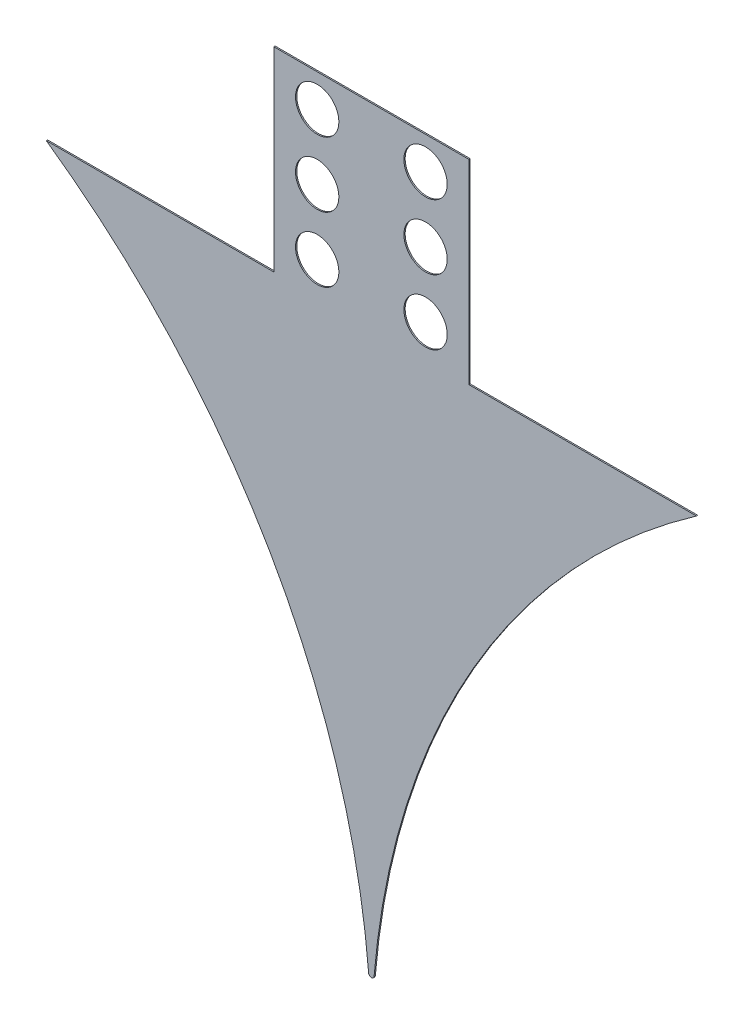
SolidWorks part; units mm, degrees
ref_plane "Front Plane" through (0, 0, 0) normal (0, 0, 1) x (1, 0, 0)
ref_plane "Top Plane" through (0, 0, 0) normal (0, 1, 0) x (1, 0, 0)
ref_plane "Right Plane" through (0, 0, 0) normal (1, 0, 0) x (0, 0, -1)
sketch "Sketch1" plane through (0, 0, 0) normal (0, 0, 1) x (1, 0, 0)
  line L0 (0, 145.9429) -> (0, -145.9429) construction
  line L1 (67, 50) -> (220, 50)
  line L2 (-67, 50) -> (-220, 50)
  line L3 (17.9555, 13) -> (15.1177, 40)
  line L4 (15.1177, 40) -> (12, 27.4955)
  line L5 (-15.1177, 40) -> (-12, 27.4955)
  line L6 (-17.9555, 13) -> (-15.1177, 40)
  line L7 (220, 50) -> (158.9525, 7.2541)
  line L8 (-220, 50) -> (-158.9525, 7.2541)
  line L9 (-140, -25) -> (-99.5632, -25)
  line L10 (140, -25) -> (99.5632, -25)
  arc A0 (67, 50) -> (17.9555, 13) centre (27.0477, 51.953) cw
  arc A1 (-67, 50) -> (-17.9555, 13) centre (-27.0477, 51.953) ccw
  arc A2 (12, 27.4955) -> (-12, 27.4955) centre (0, 0) ccw
  arc A3 (158.9525, 7.2541) -> (140, -25) centre (184.7635, -29.6077) ccw
  arc A4 (-99.5632, -25) -> (0, -115.6638) centre (-99.5632, -125) cw
  arc A5 (99.5632, -25) -> (0, -115.6638) centre (99.5632, -125) ccw
  arc A6 (-158.9525, 7.2541) -> (-140, -25) centre (-184.7635, -29.6077) cw
  dimension "D2" = 40
  dimension "D5" = 30
  dimension "D10" = 220
  dimension "D12" = 45
  dimension "D13" = 100
  dimension "D1" = 134
  dimension "D3" = 84
  dimension "D4" = 160
  dimension "D6" = 50
  dimension "D7" = 24
  dimension "D8" = 37
  dimension "D9" = 10
  dimension "D11" = 35
  dimension "D14" = 140
  dimension "D15" = 75
  dimension "D16" = 140
  dimension "D17" = 99.5632
sketch "Sketch2" plane through (0, 0, 0) normal (0, 0, 1) x (1, 0, 0)
  line L0 (0, 145.9429) -> (0, -145.9429) construction
  line L7 (0, 0) -> (0, -152.8683) construction
  line L8 (99.5632, -21.9265) -> (48.69, -83.15)
  line L9 (-99.5632, -21.9265) -> (-48.69, -83.15)
  line L26 (158.9525, 10.3276) -> (220, 53.0735)
  line L27 (220, 53.0735) -> (67, 53.0735)
  line L28 (17.9555, 16.0735) -> (15.1177, 43.0735)
  line L29 (15.1177, 43.0735) -> (12, 30.569)
  line L30 (-12, 30.569) -> (-15.1177, 43.0735)
  line L31 (-15.1177, 43.0735) -> (-17.9555, 16.0735)
  line L32 (-67, 53.0735) -> (-220, 53.0735)
  line L33 (-220, 53.0735) -> (-158.9525, 10.3276)
  line L34 (-140, -21.9265) -> (-99.5632, -21.9265)
  line L35 (99.5632, -21.9265) -> (140, -21.9265)
  circle A2 centre (46.19, 13) radius 1.5875
  circle A3 centre (-46.19, 13) radius 1.5875
  circle A4 centre (46.19, -80.65) radius 1.5875
  circle A5 centre (-46.19, -80.65) radius 1.5875
  arc A6 (48.69, -83.15) -> (0, -150) centre (70.2366, -150) ccw
  arc A7 (-48.69, -83.15) -> (0, -150) centre (-70.2366, -150) cw
  arc A14 (17.9555, 16.0735) -> (67, 53.0735) centre (27.0477, 55.0265) ccw
  arc A15 (12, 30.569) -> (-12, 30.569) centre (0, 3.0735) ccw
  arc A16 (-67, 53.0735) -> (-17.9555, 16.0735) centre (-27.0477, 55.0265) ccw
  arc A17 (-140, -21.9265) -> (-158.9525, 10.3276) centre (-184.7635, -26.5342) ccw
  arc A20 (158.9525, 10.3276) -> (140, -21.9265) centre (184.7635, -26.5342) ccw
  point P0 (0, 40)
  dimension "D3" = 93.65
  dimension "D4" = 3.175
  dimension "D5" = 3.175
  dimension "D6" = 3.175
  dimension "D7" = 3.175
  dimension "D2" = 40
  dimension "D9" = 25
  dimension "D10" = 46.19
  dimension "D11" = 27
  dimension "D12" = 46.19
  dimension "D13" = 99.5632
  dimension "D14" = 2.5
  dimension "D15" = 2.5
  dimension "D16" = 150
extrude "Boss-Extrude1" add sketch "Sketch2" along normal blind 0.118
sketch "Sketch3" plane through (0, 0, 0) normal (0, 0, -1) x (-1, 0, 0)
  line L0 (0, -121.719) -> (0, 0) construction
  line L1 (165, 49.5735) -> (165, 19.5735) construction
  line L2 (165, 19.5735) -> (165, 49.5735) construction
  line L3 (67, 53.0735) -> (220, 53.0735) construction
  circle A0 centre (165, 49.5735) radius 2
  circle A1 centre (165, 19.5735) radius 2
  circle A2 centre (150, 34.5735) radius 2
  dimension "D1" = 4
  dimension "D2" = 4
  dimension "D5" = 4
  dimension "D3" = 30
  dimension "D4" = 55
  dimension "D6" = 15
  dimension "D7" = 15
  dimension "D8" = 3.5
extrude "Cut-Extrude1" cut sketch "Sketch3" against normal through all
mirror "Mirror2" about plane through (0, 0, 0) normal (1, 0, 0) of "Cut-Extrude1"
chamfer "Chamfer1" distance 20 angle 90 2 edges at (-220, 53.0735, 0.059) (220, 53.0735, 0.059)
sketch "Sketch4" plane through (0, 0, 0) normal (0, 0, -1) x (-1, 0, 0)
  line L11 (-225.9688, 80.922) -> (214.9402, 80.922)
  line L12 (-225.9688, 80.922) -> (-225.9688, -92.431)
  line L13 (-225.9688, -92.431) -> (214.9402, -92.431)
  line L14 (214.9402, 80.922) -> (214.9402, -92.431)
  point P0 (0, -150)
  dimension "D1" = 57.569
extrude "Cut-Extrude4" cut sketch "Sketch4" against normal through all contours L11 L14 L13 L12
sketch "Sketch5" plane through (0, 0, 0) normal (0, 0, -1) x (-1, 0, 0)
  line L0 (-30, -92.431) -> (30, -92.431) construction
  line L1 (-9, -74.431) -> (9, -74.431)
  line L2 (-9, -74.431) -> (-9, -92.431)
  line L3 (-9, -92.431) -> (9, -92.431)
  line L4 (9, -74.431) -> (9, -92.431)
  line L5 (-9, -74.431) -> (9, -92.431) construction
  line L6 (-9, -92.431) -> (9, -74.431) construction
  circle A0 centre (-5, -89.431) radius 2
  circle A1 centre (5, -89.431) radius 2
  circle A2 centre (-5, -83.431) radius 2
  circle A3 centre (5, -83.431) radius 2
  circle A4 centre (-5, -77.431) radius 2
  circle A5 centre (5, -77.431) radius 2
  point P0 (0, -83.431)
  dimension "D5" = 4
  dimension "D1" = 18
  dimension "D2" = 18
  dimension "D3" = 3
  dimension "D4" = 5
  dimension "D6" = 2
  dimension "D7" = 3
extrude "Boss-Extrude2" add sketch "Sketch5" against normal up to surface (0.118 mm away) up to face at (0, -109.1714, 0.118)
fillet "Fillet1" radius 0.25 1 edges at (0, -150, 0.059)
